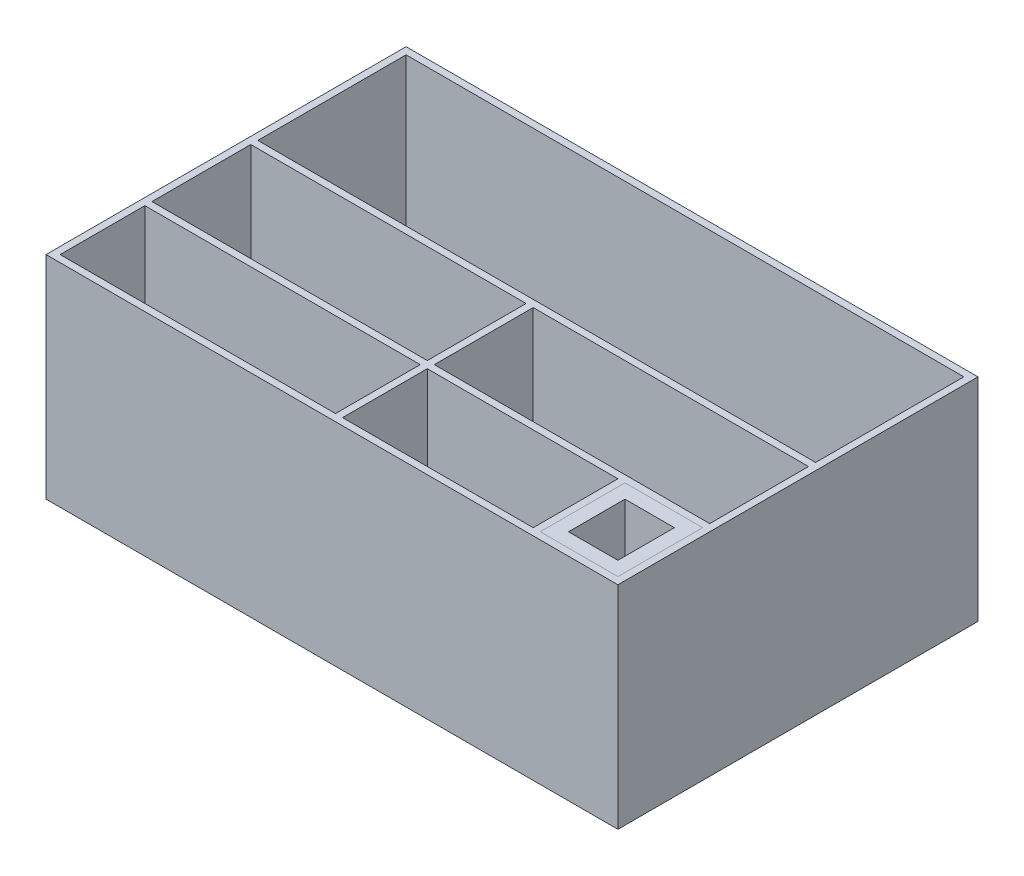
SolidWorks part; units mm, degrees
ref_plane "前视基准面" through (0, 0, 0) normal (0, 0, 1) x (1, 0, 0)
ref_plane "上视基准面" through (0, 0, 0) normal (0, 1, 0) x (1, 0, 0)
ref_plane "右视基准面" through (0, 0, 0) normal (1, 0, 0) x (0, 0, -1)
sketch "草图1" plane through (0, 0, 0) normal (0, 1, 0) x (1, 0, 0)
  line L0 (10, 290) -> (800, 290)
  line L1 (0, 510) -> (810, 510)
  line L2 (0, 510) -> (0, 0)
  line L3 (0, 0) -> (810, 0)
  line L4 (810, 510) -> (810, 0)
  line L5 (10, 500) -> (800, 500)
  line L6 (10, 500) -> (10, 290)
  line L7 (10, 10) -> (400, 10)
  line L8 (800, 500) -> (800, 290)
  line L9 (10, 280) -> (400, 280)
  line L10 (10, 140) -> (400, 140)
  line L11 (10, 130) -> (400, 130)
  line L12 (400, 280) -> (400, 140)
  line L13 (410, 280) -> (410, 140)
  line L14 (680, 130) -> (680, 10)
  line L15 (690, 130) -> (690, 10)
  line L16 (10, 280) -> (10, 140)
  line L17 (410, 140) -> (800, 140)
  line L18 (690, 130) -> (800, 130)
  line L19 (410, 130) -> (680, 130)
  line L20 (400, 130) -> (400, 10)
  line L21 (410, 130) -> (410, 10)
  line L22 (690, 10) -> (800, 10)
  line L23 (410, 10) -> (680, 10)
  line L24 (410, 280) -> (800, 280)
  line L25 (800, 130) -> (800, 10)
  line L26 (800, 280) -> (800, 140)
  line L27 (10, 130) -> (10, 10)
  dimension "D1" = 790
  dimension "D2" = 810
  dimension "D3" = 490
  dimension "D4" = 510
  dimension "D5" = 10
  dimension "D6" = 10
  dimension "D7" = 210
  dimension "D8" = 10
  dimension "D9" = 10
  dimension "D10" = 140
  dimension "D11" = 390
  dimension "D12" = 10
  dimension "D13" = 110
  dimension "D14" = 10
extrude "航空箱内部分割" add sketch "草图1" along normal blind 300
sketch "草图3" plane through (0, 0, 0) normal (0, 1, 0) x (1, 0, 0)
  line L1 (690, 130) -> (800, 130)
  line L2 (690, 130) -> (690, 10)
  line L3 (690, 10) -> (800, 10)
  line L4 (800, 130) -> (800, 10)
  line L5 (710, 110) -> (780, 110)
  line L6 (710, 110) -> (710, 30)
  line L7 (710, 30) -> (780, 30)
  line L8 (780, 110) -> (780, 30)
  dimension "D1" = 20
  dimension "D2" = 20
  dimension "D3" = 20
  dimension "D4" = 20
extrude "工具存放区泡沫" add sketch "草图3" along normal blind 300 separate body
equation "\"lowerHeight\"=300"
equation "\"D1@航空箱内部分割\"=\"lowerHeight\""
equation "\"D1@工具存放区泡沫\"=\"lowerHeight\""
